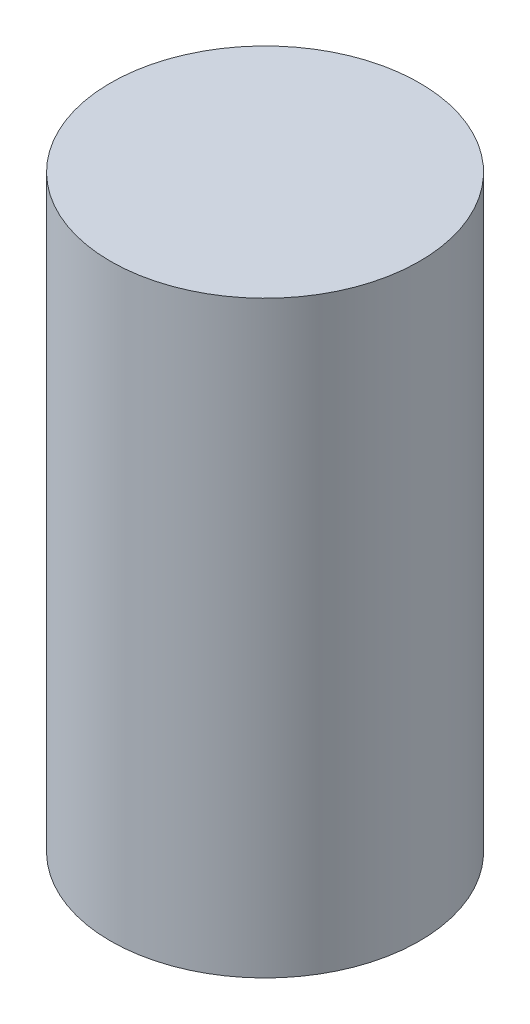
SolidWorks part; units mm, degrees
ref_plane "Front Plane" through (0, 0, 0) normal (0, 0, 1) x (1, 0, 0)
ref_plane "Top Plane" through (0, 0, 0) normal (0, 1, 0) x (1, 0, 0)
ref_plane "Right Plane" through (0, 0, 0) normal (1, 0, 0) x (0, 0, -1)
sketch "Sketch1" plane through (0, 0, 0) normal (0, 1, 0) x (1, 0, 0)
  circle A0 centre (0, 0) radius 10.5
  dimension "D1" = 21
extrude "Boss-Extrude1" add sketch "Sketch1" along normal blind 40
